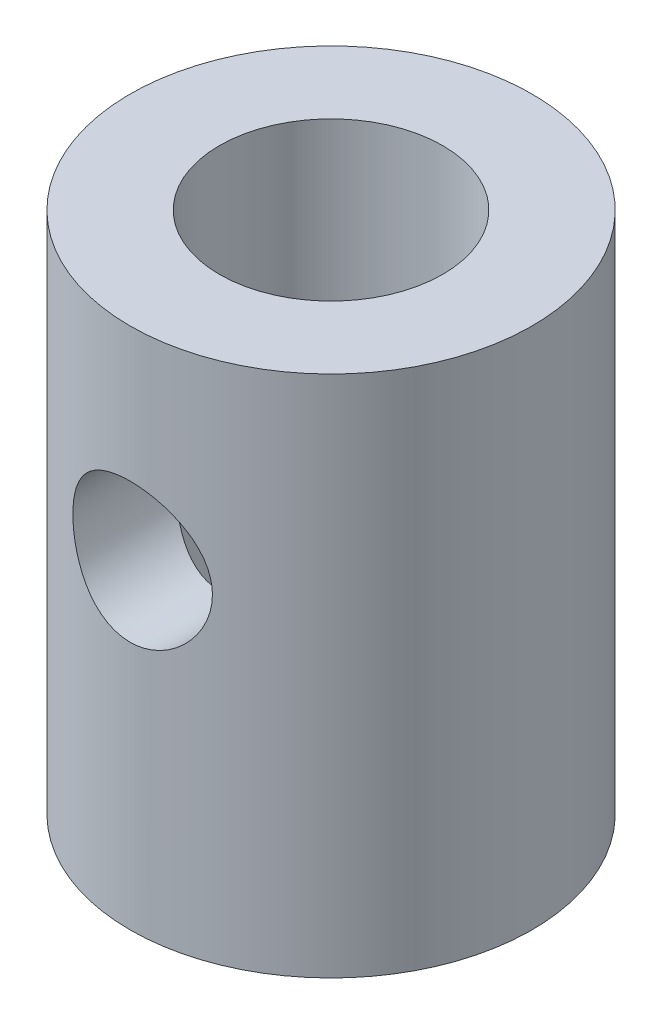
SolidWorks part; units mm, degrees
material "AISI 1020"
ref_plane "Front Plane" through (0, 0, 0) normal (0, 0, 1) x (1, 0, 0)
ref_plane "Top Plane" through (0, 0, 0) normal (0, 1, 0) x (1, 0, 0)
ref_plane "Right Plane" through (0, 0, 0) normal (1, 0, 0) x (0, 0, -1)
sketch "Sketch1" plane through (0, 0, 0) normal (0, 1, 0) x (1, 0, 0)
  circle A0 centre (0, 0) radius 8.001
  circle A1 centre (0, 0) radius 4.445
  dimension "D1" = 16.002
  dimension "D2" = 8.89
extrude "Boss-Extrude1" add sketch "Sketch1" along normal blind 20.828
ref_plane "Plane1" through (0, 0, 8.001) normal (0, 0, 1) x (1, 0, 0)
sketch "Sketch2" plane through (0, 0, 8.001) normal (0, 0, 1) x (1, 0, 0)
  line L0 (-8.001, 0) -> (8.001, 0) construction
  circle A0 centre (0, 12.7) radius 2.7788
  dimension "D1" = 12.7
  dimension "D2" = 5.5575
extrude "Cut-Extrude1" cut sketch "Sketch2" against normal blind 6.35
